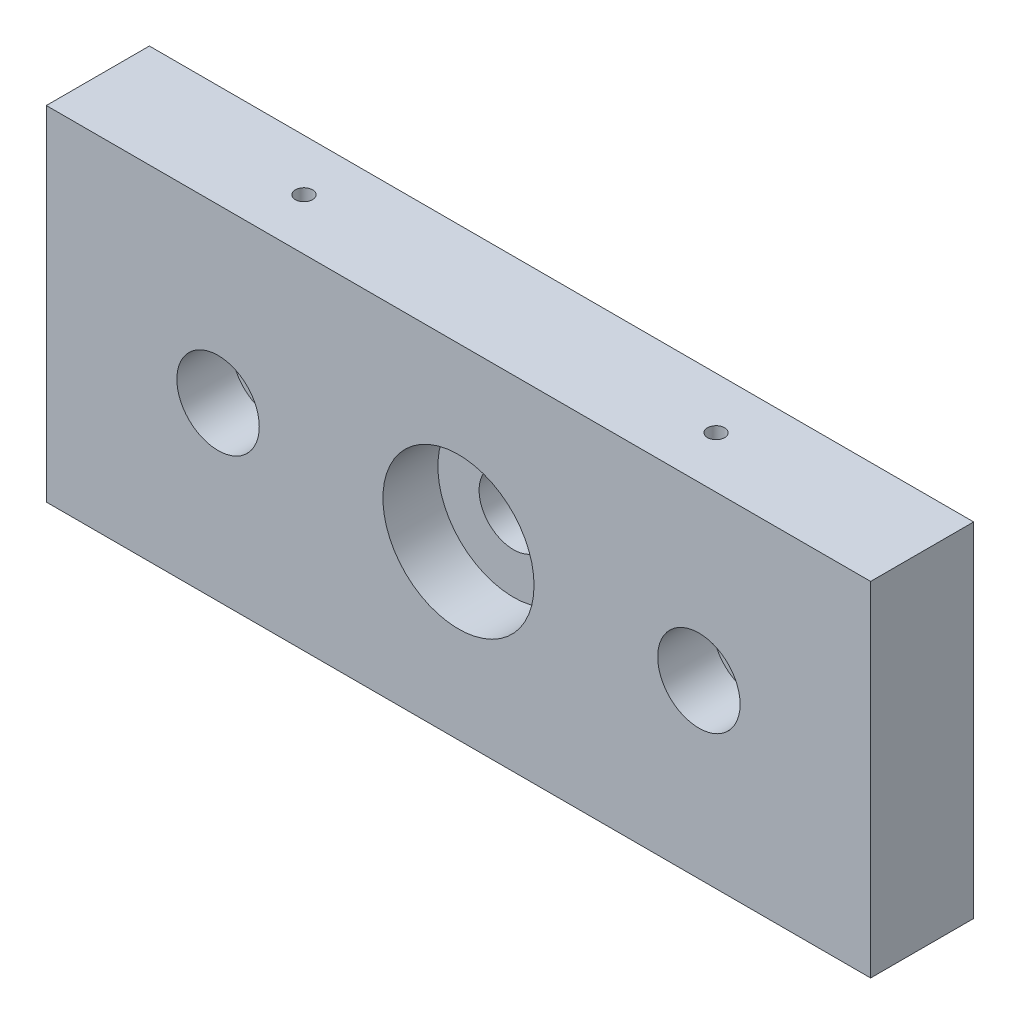
SolidWorks part; units mm, degrees
ref_plane "前视基准面" through (0, 0, 0) normal (0, 0, 1) x (1, 0, 0)
ref_plane "上视基准面" through (0, 0, 0) normal (0, 1, 0) x (1, 0, 0)
ref_plane "右视基准面" through (0, 0, 0) normal (1, 0, 0) x (0, 0, -1)
sketch "草图1" plane through (0, 0, 0) normal (0, 0, 1) x (1, 0, 0)
  line L0 (60, 25) -> (-60, -25) construction
  line L1 (-60, -25) -> (60, -25)
  line L2 (-60, -25) -> (-60, 25)
  line L3 (-60, 25) -> (60, 25)
  line L4 (60, -25) -> (60, 25)
  line L5 (-60, 25) -> (60, -25) construction
  point P4 (0, 0)
  dimension "D1" = 120
  dimension "D2" = 50
extrude "凸台-拉伸1" add sketch "草图1" along normal blind 15
sketch "草图2" plane through (0, 0, 15) normal (0, 0, 1) x (1, 0, 0)
  line L0 (0, 25) -> (0, -25) construction
  line L1 (60, 25) -> (-60, 25) construction
  line L2 (-60, -25) -> (60, -25) construction
  line L3 (-60, 0) -> (60, 0) construction
  line L4 (-60, 25) -> (-60, -25) construction
  line L5 (60, -25) -> (60, 25) construction
  circle A0 centre (-35, 0) radius 6
  circle A1 centre (35, 0) radius 6
  dimension "D2" = 12
  dimension "D3" = 70
extrude "切除-拉伸1" cut sketch "草图2" against normal blind 8
sketch "草图3" plane through (0, 0, 15) normal (0, 0, 1) x (1, 0, 0)
  circle A0 centre (0, 0) radius 11
  dimension "D1" = 22
extrude "切除-拉伸2" cut sketch "草图3" against normal blind 8
sketch "草图10" plane through (0, 0, 7) normal (0, 0, 1) x (1, 0, 0)
  circle A0 centre (-35, 0) radius 3.25
  circle A1 centre (35, 0) radius 3.25
  dimension "D1" = 6.5
  dimension "D2" = 6.5
extrude "切除-拉伸4" cut sketch "草图10" against normal blind 10
sketch "草图11" plane through (0, 0, 7) normal (0, 0, 1) x (1, 0, 0)
  circle A0 centre (0, 0) radius 5
  dimension "D1" = 10
extrude "切除-拉伸5" cut sketch "草图11" against normal blind 10
sketch "草图12" plane through (0, 25, 0) normal (0, 1, 0) x (1, 0, 0)
  line L0 (0, 0) -> (60, -15) construction
  line L1 (60, 0) -> (0, -15) construction
  line L2 (60, -15) -> (-60, -15) construction
  line L3 (0, 0) -> (0, -15) construction
  point P9 (30, -7.5)
  point P10 (-30, -7.5)
hole_wizard "M3 螺纹孔1" positions "草图13" profile "草图14" tap size "M3" standard "GB"
sketch "草图13" plane through (0, 25, 0) normal (0, 1, 0) x (1, 0, 0)
  line L0 (0, 0) -> (60, -15) construction
  point P0 (30, -7.5)
  point P4 (-30, -7.5)
sketch "草图14" plane through (30, 25, 7.5) normal (1, 0, 0) x (0, 0, 1)
  line L0 (0, 0) -> (0, 5.7511)
  line L1 (0, 5.7511) -> (1.25, 5)
  line L2 (1.25, 5) -> (1.25, 0)
  line L5 (1.25, 0) -> (0, 0)
  line L10 (0, 5.7511) -> (-1.25, 5) construction
  line L11 (0, -6.35) -> (0, 107.95) construction
  dimension "螺纹孔钻头直径" = 2.5
  dimension "螺纹孔钻头深度" = 5
  dimension "导头角度" = 118
cosmetic thread "孔螺蚊线1" parameters "D1"=5, "D2"=3
cosmetic thread "孔螺蚊线2" parameters "D1"=5, "D2"=3
hole_wizard "M3 螺纹孔2" positions "草图18" profile "草图17" tap size "M3" standard "GB"
sketch "草图18" plane through (0, -25, 0) normal (0, -1, 0) x (-1, 0, 0)
  line L0 (0, 0) -> (-60, -15) construction
  point P0 (-30, -7.5)
  point P4 (30, -7.5)
sketch "草图17" plane through (30, -25, 7.5) normal (1, 0, 0) x (0, 0, -1)
  line L0 (0, 0) -> (0, 5.7511)
  line L1 (0, 5.7511) -> (1.25, 5)
  line L2 (1.25, 5) -> (1.25, 0)
  line L5 (1.25, 0) -> (0, 0)
  line L10 (0, 5.7511) -> (-1.25, 5) construction
  line L11 (0, -6.35) -> (0, 107.95) construction
  dimension "螺纹孔钻头直径" = 2.5
  dimension "螺纹孔钻头深度" = 5
  dimension "导头角度" = 118
cosmetic thread "孔螺蚊线3" parameters "D1"=5, "D2"=3
cosmetic thread "孔螺蚊线4" parameters "D1"=5, "D2"=3
